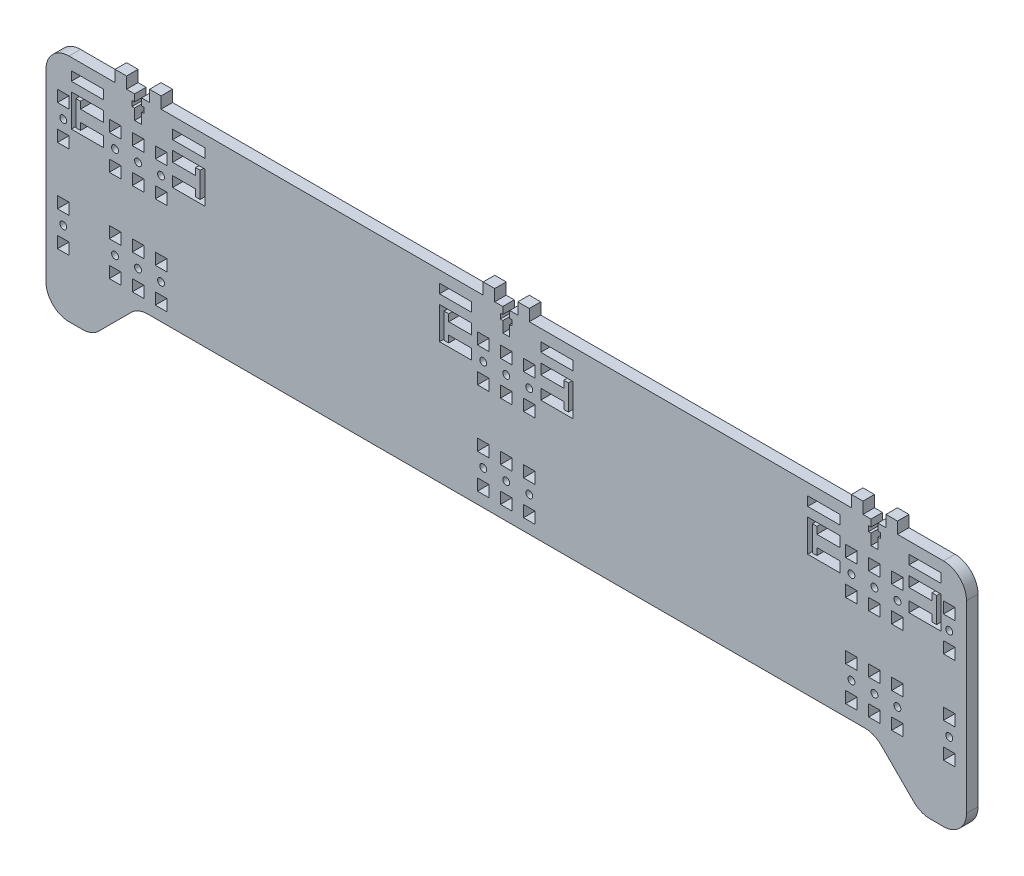
SolidWorks part; units mm, degrees
ref_plane "Front Plane" through (0, 0, 0) normal (0, 0, 1) x (1, 0, 0)
ref_plane "Top Plane" through (0, 0, 0) normal (0, 1, 0) x (1, 0, 0)
ref_plane "Right Plane" through (0, 0, 0) normal (1, 0, 0) x (0, 0, -1)
sketch "Sketch1" plane through (0, 0, 0) normal (0, 0, 1) x (1, 0, 0)
  line L0 (0, 0) -> (194.9917, 0) construction
  line L1 (0, 0) -> (0, -11.2208) construction
  line L2 (1.5, 0) -> (5, 0)
  line L3 (5, 5) -> (10, 5)
  line L4 (10, 5) -> (10, 0)
  line L5 (5, 5) -> (5, 0)
  line L6 (-1.5, 0) -> (-5, 0)
  line L7 (-5, 0) -> (-5, 5)
  line L8 (-5, 5) -> (-10, 5)
  line L9 (-10, 5) -> (-10, 0)
  line L10 (1.5, 0) -> (-1.5, 0) construction
  line L11 (-1.5, 0) -> (-1.5, -3)
  line L12 (-1.5, -5.3) -> (-2.6, -5.3)
  line L13 (2.6, -3) -> (2.6, -5.3)
  line L14 (-2.6, -3) -> (-1.5, -3)
  line L15 (-1.5, -5.3) -> (-1.5, -10)
  line L16 (-1.5, -10) -> (1.5, -10)
  line L17 (1.5, -10) -> (1.5, -5.3)
  line L18 (1.5, -3) -> (2.6, -3)
  line L19 (-2.6, -5.3) -> (-2.6, -3)
  line L20 (2.6, -5.3) -> (1.5, -5.3)
  line L21 (1.5, -3) -> (1.5, 0)
  line L22 (0, -10) -> (0, 0) construction
  line L23 (170, 5) -> (170, 0)
  line L24 (165, 5) -> (170, 5)
  line L25 (165, 5) -> (165, 0)
  line L26 (161.5, 0) -> (165, 0)
  line L27 (161.5, -3) -> (161.5, 0)
  line L28 (161.5, -3) -> (162.6, -3)
  line L29 (162.6, -3) -> (162.6, -5.3)
  line L30 (162.6, -5.3) -> (161.5, -5.3)
  line L31 (161.5, -10) -> (161.5, -5.3)
  line L32 (158.5, -10) -> (161.5, -10)
  line L33 (158.5, -5.3) -> (158.5, -10)
  line L34 (158.5, -5.3) -> (157.4, -5.3)
  line L35 (157.4, -5.3) -> (157.4, -3)
  line L36 (157.4, -3) -> (158.5, -3)
  line L37 (158.5, 0) -> (158.5, -3)
  line L38 (158.5, 0) -> (155, 0)
  line L39 (155, 0) -> (155, 5)
  line L40 (155, 5) -> (150, 5)
  line L41 (150, 5) -> (150, 0)
  line L42 (0, 0) -> (0, -65) construction
  line L43 (-150, 5) -> (-150, 0)
  line L44 (-155, 5) -> (-150, 5)
  line L45 (-155, 0) -> (-155, 5)
  line L46 (-158.5, 0) -> (-155, 0)
  line L47 (-158.5, 0) -> (-158.5, -3)
  line L48 (-157.4, -3) -> (-158.5, -3)
  line L49 (-157.4, -5.3) -> (-157.4, -3)
  line L50 (-158.5, -5.3) -> (-157.4, -5.3)
  line L51 (-158.5, -5.3) -> (-158.5, -10)
  line L52 (-158.5, -10) -> (-161.5, -10)
  line L53 (-161.5, -10) -> (-161.5, -5.3)
  line L54 (-162.6, -5.3) -> (-161.5, -5.3)
  line L55 (-162.6, -3) -> (-162.6, -5.3)
  line L56 (-161.5, -3) -> (-162.6, -3)
  line L57 (-161.5, -3) -> (-161.5, 0)
  line L58 (-161.5, 0) -> (-165, 0)
  line L59 (-165, 5) -> (-165, 0)
  line L60 (-165, 5) -> (-170, 5)
  line L61 (-170, 5) -> (-170, 0)
  line L63 (-10, 0) -> (-150, 0)
  line L64 (-170, 0) -> (-200, 0)
  line L65 (-200, 0) -> (-200, -100)
  line L66 (-200, -100) -> (200, -100) construction
  line L67 (200, -100) -> (200, 0)
  line L68 (200, 0) -> (170, 0)
  line L69 (10, 0) -> (150, 0)
  line L70 (-200, -65) -> (200, -65) construction
  line L71 (-160, -10) -> (-160, -65) construction
  line L72 (160, -10) -> (160, -65) construction
  line L73 (-150, -25) -> (-150, -65) construction
  line L74 (-200, -100) -> (-180, -100)
  line L75 (-180, -100) -> (-160, -80)
  line L76 (-160, -80) -> (160, -80)
  line L77 (160, -80) -> (180, -100)
  line L78 (180, -100) -> (200, -100)
  point P31 (0, -34.8981)
  point P84 (0, 0)
  point P85 (0, 0)
  point P86 (0, 0)
  point P87 (0, 0)
  point P88 (0, 0)
  point P89 (-167.5, -20)
  point P90 (-167.5, -20)
  point P91 (167.5, -20)
  point P92 (0, -60)
  point P93 (0, -20)
  point P94 (0, 0)
  point P95 (2.6, -30)
  point P96 (-160, -22.4475)
  point P97 (0, 0)
  point P98 (-160, -60)
  point P99 (48.9382, -34.8981)
  point P100 (160, -20)
  point P101 (0, 0)
  point P102 (0, 0)
  point P103 (160, -65)
  point P104 (157.4, -60)
  line B0 (150, -60) -> (150, -70) construction
  line B1 (152.5, -60) -> (152.5, -55)
  line B2 (152.5, -60) -> (147.5, -60)
  line B3 (147.5, -60) -> (147.5, -55)
  line B4 (152.5, -55) -> (147.5, -55)
  line B5 (152.5, -70) -> (152.5, -75)
  line B6 (152.5, -70) -> (147.5, -70)
  line B7 (147.5, -70) -> (147.5, -75)
  line B8 (152.5, -75) -> (147.5, -75)
  line B9 (150, -65) -> (156.9724, -65) construction
  circle B10 centre (150, -65) radius 1.5
  line B11 (10, -60) -> (10, -70) construction
  line B12 (12.5, -60) -> (12.5, -55)
  line B13 (12.5, -60) -> (7.5, -60)
  line B14 (7.5, -60) -> (7.5, -55)
  line B15 (12.5, -55) -> (7.5, -55)
  line B16 (12.5, -70) -> (12.5, -75)
  line B17 (12.5, -70) -> (7.5, -70)
  line B18 (7.5, -70) -> (7.5, -75)
  line B19 (12.5, -75) -> (7.5, -75)
  line B20 (10, -65) -> (16.9724, -65) construction
  circle B21 centre (10, -65) radius 1.5
  line B22 (-150, -60) -> (-150, -70) construction
  line B23 (-147.5, -60) -> (-147.5, -55)
  line B24 (-147.5, -60) -> (-152.5, -60)
  line B25 (-152.5, -60) -> (-152.5, -55)
  line B26 (-147.5, -55) -> (-152.5, -55)
  line B27 (-147.5, -70) -> (-147.5, -75)
  line B28 (-147.5, -70) -> (-152.5, -70)
  line B29 (-152.5, -70) -> (-152.5, -75)
  line B30 (-147.5, -75) -> (-152.5, -75)
  line B31 (-150, -65) -> (-143.0276, -65) construction
  circle B32 centre (-150, -65) radius 1.5
  line B33 (-150, -20) -> (-150, -30) construction
  line B34 (-147.5, -20) -> (-147.5, -15)
  line B35 (-147.5, -20) -> (-152.5, -20)
  line B36 (-152.5, -20) -> (-152.5, -15)
  line B37 (-147.5, -15) -> (-152.5, -15)
  line B38 (-147.5, -30) -> (-147.5, -35)
  line B39 (-147.5, -30) -> (-152.5, -30)
  line B40 (-152.5, -30) -> (-152.5, -35)
  line B41 (-147.5, -35) -> (-152.5, -35)
  line B42 (-150, -25) -> (-143.0276, -25) construction
  circle B43 centre (-150, -25) radius 1.5
  line B44 (10, -20) -> (10, -30) construction
  line B45 (12.5, -20) -> (12.5, -15)
  line B46 (12.5, -20) -> (7.5, -20)
  line B47 (7.5, -20) -> (7.5, -15)
  line B48 (12.5, -15) -> (7.5, -15)
  line B49 (12.5, -30) -> (12.5, -35)
  line B50 (12.5, -30) -> (7.5, -30)
  line B51 (7.5, -30) -> (7.5, -35)
  line B52 (12.5, -35) -> (7.5, -35)
  line B53 (10, -25) -> (16.9724, -25) construction
  circle B54 centre (10, -25) radius 1.5
  line B55 (150, -20) -> (150, -30) construction
  line B56 (152.5, -20) -> (152.5, -15)
  line B57 (152.5, -20) -> (147.5, -20)
  line B58 (147.5, -20) -> (147.5, -15)
  line B59 (152.5, -15) -> (147.5, -15)
  line B60 (152.5, -30) -> (152.5, -35)
  line B61 (152.5, -30) -> (147.5, -30)
  line B62 (147.5, -30) -> (147.5, -35)
  line B63 (152.5, -35) -> (147.5, -35)
  line B64 (150, -25) -> (156.9724, -25) construction
  circle B65 centre (150, -25) radius 1.5
  line B66 (192.5, -20) -> (192.5, -30) construction
  line B67 (195, -20) -> (195, -15)
  line B68 (195, -20) -> (190, -20)
  line B69 (190, -20) -> (190, -15)
  line B70 (195, -15) -> (190, -15)
  line B71 (195, -30) -> (195, -35)
  line B72 (195, -30) -> (190, -30)
  line B73 (190, -30) -> (190, -35)
  line B74 (195, -35) -> (190, -35)
  line B75 (192.5, -25) -> (199.4724, -25) construction
  circle B76 centre (192.5, -25) radius 1.5
  line B77 (192.5, -60) -> (192.5, -70) construction
  line B78 (195, -60) -> (195, -55)
  line B79 (195, -60) -> (190, -60)
  line B80 (190, -60) -> (190, -55)
  line B81 (195, -55) -> (190, -55)
  line B82 (195, -70) -> (195, -75)
  line B83 (195, -70) -> (190, -70)
  line B84 (190, -70) -> (190, -75)
  line B85 (195, -75) -> (190, -75)
  line B86 (192.5, -65) -> (199.4724, -65) construction
  circle B87 centre (192.5, -65) radius 1.5
  line B88 (-192.5, -60) -> (-192.5, -70) construction
  line B89 (-190, -60) -> (-190, -55)
  line B90 (-190, -60) -> (-195, -60)
  line B91 (-195, -60) -> (-195, -55)
  line B92 (-190, -55) -> (-195, -55)
  line B93 (-190, -70) -> (-190, -75)
  line B94 (-190, -70) -> (-195, -70)
  line B95 (-195, -70) -> (-195, -75)
  line B96 (-190, -75) -> (-195, -75)
  line B97 (-192.5, -65) -> (-185.5276, -65) construction
  circle B98 centre (-192.5, -65) radius 1.5
  line B99 (-192.5, -20) -> (-192.5, -30) construction
  line B100 (-190, -20) -> (-190, -15)
  line B101 (-190, -20) -> (-195, -20)
  line B102 (-195, -20) -> (-195, -15)
  line B103 (-190, -15) -> (-195, -15)
  line B104 (-190, -30) -> (-190, -35)
  line B105 (-190, -30) -> (-195, -30)
  line B106 (-195, -30) -> (-195, -35)
  line B107 (-190, -35) -> (-195, -35)
  line B108 (-192.5, -25) -> (-185.5276, -25) construction
  circle B109 centre (-192.5, -25) radius 1.5
  line B110 (172.5, -20) -> (172.5, -15)
  line B111 (172.5, -20) -> (167.5, -20)
  line B112 (167.5, -20) -> (167.5, -15)
  line B113 (172.5, -15) -> (167.5, -15)
  line B114 (172.5, -30) -> (172.5, -35)
  line B115 (172.5, -30) -> (167.5, -30)
  line B116 (167.5, -30) -> (167.5, -35)
  line B117 (172.5, -35) -> (167.5, -35)
  line B118 (170, -25) -> (176.9724, -25) construction
  circle B119 centre (170, -25) radius 1.5
  line B120 (172.5, -60) -> (172.5, -55)
  line B121 (172.5, -60) -> (167.5, -60)
  line B122 (167.5, -60) -> (167.5, -55)
  line B123 (172.5, -55) -> (167.5, -55)
  line B124 (172.5, -70) -> (172.5, -75)
  line B125 (172.5, -70) -> (167.5, -70)
  line B126 (167.5, -70) -> (167.5, -75)
  line B127 (172.5, -75) -> (167.5, -75)
  line B128 (170, -65) -> (176.9724, -65) construction
  circle B129 centre (170, -65) radius 1.5
  line B130 (-12.5, -60) -> (-12.5, -55)
  line B131 (-12.5, -60) -> (-7.5, -60)
  line B132 (-7.5, -60) -> (-7.5, -55)
  line B133 (-12.5, -55) -> (-7.5, -55)
  line B134 (-12.5, -70) -> (-12.5, -75)
  line B135 (-12.5, -70) -> (-7.5, -70)
  line B136 (-7.5, -70) -> (-7.5, -75)
  line B137 (-12.5, -75) -> (-7.5, -75)
  circle B138 centre (-10, -65) radius 1.5
  line B139 (-12.5, -20) -> (-12.5, -15)
  line B140 (-12.5, -20) -> (-7.5, -20)
  line B141 (-7.5, -20) -> (-7.5, -15)
  line B142 (-12.5, -15) -> (-7.5, -15)
  line B143 (-12.5, -30) -> (-12.5, -35)
  line B144 (-12.5, -30) -> (-7.5, -30)
  line B145 (-7.5, -30) -> (-7.5, -35)
  line B146 (-12.5, -35) -> (-7.5, -35)
  line B147 (-10, -25) -> (-16.9724, -25) construction
  circle B148 centre (-10, -25) radius 1.5
  line B149 (-172.5, -60) -> (-172.5, -55)
  line B150 (-172.5, -60) -> (-167.5, -60)
  line B151 (-167.5, -60) -> (-167.5, -55)
  line B152 (-172.5, -55) -> (-167.5, -55)
  line B153 (-172.5, -70) -> (-172.5, -75)
  line B154 (-172.5, -70) -> (-167.5, -70)
  line B155 (-167.5, -70) -> (-167.5, -75)
  line B156 (-172.5, -75) -> (-167.5, -75)
  circle B157 centre (-170, -65) radius 1.5
  line B158 (-172.5, -20) -> (-172.5, -15)
  line B159 (-172.5, -20) -> (-167.5, -20)
  line B160 (-167.5, -20) -> (-167.5, -15)
  line B161 (-172.5, -15) -> (-167.5, -15)
  line B162 (-172.5, -30) -> (-172.5, -35)
  line B163 (-172.5, -30) -> (-167.5, -30)
  line B164 (-167.5, -30) -> (-167.5, -35)
  line B165 (-172.5, -35) -> (-167.5, -35)
  circle B166 centre (-170, -25) radius 1.5
  line B167 (-145, -17.5) -> (-135, -17.5)
  line B168 (-145, -5) -> (-131, -5)
  line B169 (-145, -5) -> (-145, -9)
  line B170 (-145, -9) -> (-131, -9)
  line B171 (-131, -5) -> (-131, -9)
  line B172 (-135, -17.5) -> (-135, -14.5)
  line B173 (-135, -14.5) -> (-133, -14.5)
  line B174 (-133, -14.5) -> (-133, -25.5)
  line B175 (-133, -25.5) -> (-135, -25.5)
  line B176 (-135, -25.5) -> (-135, -22.5)
  line B177 (-135, -22.5) -> (-145, -22.5)
  line B178 (-145, -22.5) -> (-145, -27)
  line B179 (-145, -27) -> (-131, -27)
  line B180 (-131, -27) -> (-131, -13)
  line B181 (-131, -13) -> (-145, -13)
  line B182 (-145, -13) -> (-145, -17.5)
  line B183 (15, -17.5) -> (25, -17.5)
  line B184 (15, -5) -> (29, -5)
  line B185 (15, -5) -> (15, -9)
  line B186 (15, -9) -> (29, -9)
  line B187 (29, -5) -> (29, -9)
  line B188 (25, -17.5) -> (25, -14.5)
  line B189 (25, -14.5) -> (27, -14.5)
  line B190 (27, -14.5) -> (27, -25.5)
  line B191 (27, -25.5) -> (25, -25.5)
  line B192 (25, -25.5) -> (25, -22.5)
  line B193 (25, -22.5) -> (15, -22.5)
  line B194 (15, -22.5) -> (15, -27)
  line B195 (15, -27) -> (29, -27)
  line B196 (29, -27) -> (29, -13)
  line B197 (29, -13) -> (15, -13)
  line B198 (15, -13) -> (15, -17.5)
  line B199 (175, -17.5) -> (185, -17.5)
  line B200 (175, -5) -> (189, -5)
  line B201 (175, -5) -> (175, -9)
  line B202 (175, -9) -> (189, -9)
  line B203 (189, -5) -> (189, -9)
  line B204 (185, -17.5) -> (185, -14.5)
  line B205 (185, -14.5) -> (187, -14.5)
  line B206 (187, -14.5) -> (187, -25.5)
  line B207 (187, -25.5) -> (185, -25.5)
  line B208 (185, -25.5) -> (185, -22.5)
  line B209 (185, -22.5) -> (175, -22.5)
  line B210 (175, -22.5) -> (175, -27)
  line B211 (175, -27) -> (189, -27)
  line B212 (189, -27) -> (189, -13)
  line B213 (189, -13) -> (175, -13)
  line B214 (175, -13) -> (175, -17.5)
  line B215 (145, -17.5) -> (135, -17.5)
  line B216 (145, -5) -> (131, -5)
  line B217 (145, -5) -> (145, -9)
  line B218 (145, -9) -> (131, -9)
  line B219 (131, -5) -> (131, -9)
  line B220 (135, -17.5) -> (135, -14.5)
  line B221 (135, -14.5) -> (133, -14.5)
  line B222 (133, -14.5) -> (133, -25.5)
  line B223 (133, -25.5) -> (135, -25.5)
  line B224 (135, -25.5) -> (135, -22.5)
  line B225 (135, -22.5) -> (145, -22.5)
  line B226 (145, -22.5) -> (145, -27)
  line B227 (145, -27) -> (131, -27)
  line B228 (131, -27) -> (131, -13)
  line B229 (131, -13) -> (145, -13)
  line B230 (145, -13) -> (145, -17.5)
  line B231 (-15, -17.5) -> (-25, -17.5)
  line B232 (-15, -5) -> (-29, -5)
  line B233 (-15, -5) -> (-15, -9)
  line B234 (-15, -9) -> (-29, -9)
  line B235 (-29, -5) -> (-29, -9)
  line B236 (-25, -17.5) -> (-25, -14.5)
  line B237 (-25, -14.5) -> (-27, -14.5)
  line B238 (-27, -14.5) -> (-27, -25.5)
  line B239 (-27, -25.5) -> (-25, -25.5)
  line B240 (-25, -25.5) -> (-25, -22.5)
  line B241 (-25, -22.5) -> (-15, -22.5)
  line B242 (-15, -22.5) -> (-15, -27)
  line B243 (-15, -27) -> (-29, -27)
  line B244 (-29, -27) -> (-29, -13)
  line B245 (-29, -13) -> (-15, -13)
  line B246 (-15, -13) -> (-15, -17.5)
  line B247 (-175, -17.5) -> (-185, -17.5)
  line B248 (-175, -5) -> (-189, -5)
  line B249 (-175, -5) -> (-175, -9)
  line B250 (-175, -9) -> (-189, -9)
  line B251 (-189, -5) -> (-189, -9)
  line B252 (-185, -17.5) -> (-185, -14.5)
  line B253 (-185, -14.5) -> (-187, -14.5)
  line B254 (-187, -14.5) -> (-187, -25.5)
  line B255 (-187, -25.5) -> (-185, -25.5)
  line B256 (-185, -25.5) -> (-185, -22.5)
  line B257 (-185, -22.5) -> (-175, -22.5)
  line B258 (-175, -22.5) -> (-175, -27)
  line B259 (-175, -27) -> (-189, -27)
  line B260 (-189, -27) -> (-189, -13)
  line B261 (-189, -13) -> (-175, -13)
  line B262 (-175, -13) -> (-175, -17.5)
  line B263 (2.5, -60) -> (2.5, -55)
  line B264 (2.5, -60) -> (-2.5, -60)
  line B265 (-2.5, -60) -> (-2.5, -55)
  line B266 (2.5, -55) -> (-2.5, -55)
  line B267 (2.5, -70) -> (2.5, -75)
  line B268 (2.5, -70) -> (-2.5, -70)
  line B269 (-2.5, -70) -> (-2.5, -75)
  line B270 (2.5, -75) -> (-2.5, -75)
  circle B271 centre (0, -65) radius 1.5
  line B272 (2.5, -20) -> (2.5, -15)
  line B273 (2.5, -20) -> (-2.5, -20)
  line B274 (-2.5, -20) -> (-2.5, -15)
  line B275 (2.5, -15) -> (-2.5, -15)
  line B276 (2.5, -30) -> (2.5, -35)
  line B277 (2.5, -30) -> (-2.5, -30)
  line B278 (-2.5, -30) -> (-2.5, -35)
  line B279 (2.5, -35) -> (-2.5, -35)
  line B280 (0, -25) -> (6.9724, -25) construction
  circle B281 centre (0, -25) radius 1.5
  line B282 (-157.5, -20) -> (-157.5, -15)
  line B283 (-157.5, -20) -> (-162.5, -20)
  line B284 (-162.5, -20) -> (-162.5, -15)
  line B285 (-157.5, -15) -> (-162.5, -15)
  line B286 (-157.5, -30) -> (-157.5, -35)
  line B287 (-157.5, -30) -> (-162.5, -30)
  line B288 (-162.5, -30) -> (-162.5, -35)
  line B289 (-157.5, -35) -> (-162.5, -35)
  line B290 (-160, -25) -> (-153.0276, -25) construction
  circle B291 centre (-160, -25) radius 1.5
  line B292 (-157.5, -60) -> (-157.5, -55)
  line B293 (-157.5, -60) -> (-162.5, -60)
  line B294 (-162.5, -60) -> (-162.5, -55)
  line B295 (-157.5, -55) -> (-162.5, -55)
  line B296 (-157.5, -70) -> (-157.5, -75)
  line B297 (-157.5, -70) -> (-162.5, -70)
  line B298 (-162.5, -70) -> (-162.5, -75)
  line B299 (-157.5, -75) -> (-162.5, -75)
  circle B300 centre (-160, -65) radius 1.5
  line B301 (162.5, -20) -> (162.5, -15)
  line B302 (162.5, -20) -> (157.5, -20)
  line B303 (157.5, -20) -> (157.5, -15)
  line B304 (162.5, -15) -> (157.5, -15)
  line B305 (162.5, -30) -> (162.5, -35)
  line B306 (162.5, -30) -> (157.5, -30)
  line B307 (157.5, -30) -> (157.5, -35)
  line B308 (162.5, -35) -> (157.5, -35)
  line B309 (160, -25) -> (166.9724, -25) construction
  circle B310 centre (160, -25) radius 1.5
  line B311 (162.5, -60) -> (162.5, -55)
  line B312 (162.5, -60) -> (157.5, -60)
  line B313 (157.5, -60) -> (157.5, -55)
  line B314 (162.5, -55) -> (157.5, -55)
  line B315 (162.5, -70) -> (162.5, -75)
  line B316 (162.5, -70) -> (157.5, -70)
  line B317 (157.5, -70) -> (157.5, -75)
  line B318 (162.5, -75) -> (157.5, -75)
  line B319 (160, -65) -> (166.9724, -65) construction
  circle B320 centre (160, -65) radius 1.5
  dimension "D1" = 10
  dimension "D2" = 25
  dimension "D3" = 5
  dimension "D4" = 5.2
  dimension "D5" = 3
  dimension "D6" = 2.3
  dimension "D7" = 3
  dimension "D8" = 10
  dimension "D10" = 40
  dimension "D11" = 30
  dimension "D12" = 100
  dimension "D13" = 160
  dimension "D14" = 10
  dimension "D15" = 5
  dimension "D16" = 10
  dimension "D17" = 10
  dimension "D18" = 5
  dimension "D19" = 20
  dimension "D20" = 80
  dimension "D21" = 20
  dimension "D24" = 15
  dimension "D27" = 15
  dimension "D28" = 15
  dimension "D9" = 2
sketch_block_instance "Trou M3 plots 5mm-1"
sketch_block "Block1" parameters "D2"=3, "D1"=5, "D3"=5, "D4"=10
sketch_block_instance "Block1-1"
sketch_block_instance "Block1-2"
sketch_block_instance "Block1-3"
sketch_block_instance "Block1-4"
sketch_block_instance "Block1-5"
sketch_block_instance "Block1-7"
sketch_block_instance "Block1-8"
sketch_block_instance "Block1-9"
sketch_block_instance "Block1-10"
sketch_block_instance "Block1-16"
sketch_block_instance "Block1-17"
sketch_block_instance "Block1-27"
sketch_block_instance "Block1-28"
sketch_block_instance "Block1-29"
sketch_block_instance "Block1-30"
sketch_block_instance "Bloc1-5"
sketch_block "Bloc1" parameters "D1"=10, "D2"=2, "D3"=2, "D4"=3, "D5"=1.5, "D6"=5, "D7"=4, "D8"=4
sketch_block_instance "Bloc1-6"
sketch_block_instance "Bloc1-7"
sketch_block_instance "Bloc1-8"
sketch_block_instance "Bloc1-9"
sketch_block_instance "Bloc1-10"
sketch_block_instance "Block1-31"
sketch_block_instance "Block1-32"
sketch_block_instance "Block1-35"
sketch_block_instance "Block1-36"
sketch_block_instance "Block1-37"
sketch_block_instance "Block1-38"
extrude "Boss-Extrude1" add sketch "Sketch1" along normal blind 5
fillet "Congé1" radius 10 8 edges at (200, 0, 2.5) (-200, 0, 2.5) (200, -100, 2.5) (180, -100, 2.5) (160, -80, 2.5) (-160, -80, 2.5) (-180, -100, 2.5) (-200, -100, 2.5)
